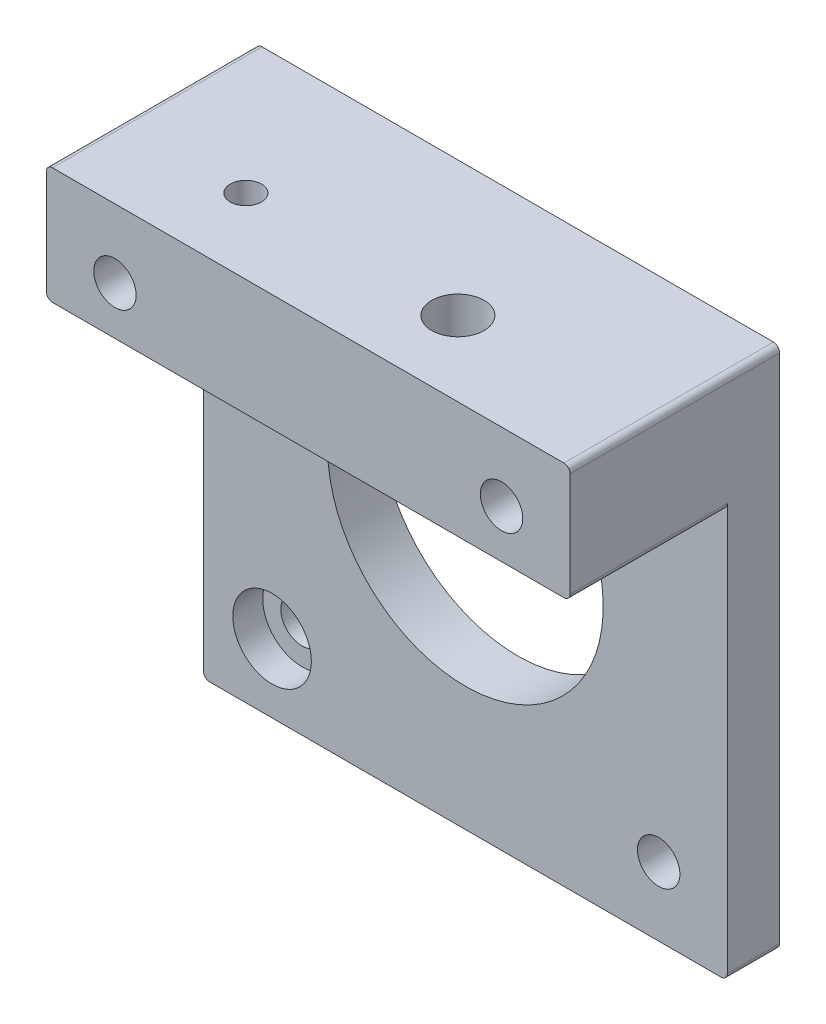
SolidWorks part; units mm, degrees
ref_plane "Front Plane" through (0, 0, 0) normal (0, 0, 1) x (1, 0, 0)
ref_plane "Top Plane" through (0, 0, 0) normal (0, 1, 0) x (1, 0, 0)
ref_plane "Right Plane" through (0, 0, 0) normal (1, 0, 0) x (0, 0, -1)
sketch "Sketch1" plane through (0, 0, 0) normal (0, 0, 1) x (1, 0, 0)
  line L1 (-21, 21) -> (21, 21)
  line L2 (-21, 21) -> (-21, -21)
  line L3 (-21, -21) -> (21, -21)
  line L4 (21, 21) -> (21, -21)
  line L5 (-21, 21) -> (21, -21) construction
  line L6 (-21, -21) -> (21, 21) construction
  point P0 (0, 0)
  dimension "D1" = 42
  dimension "D2" = 42
extrude "Boss-Extrude1" add sketch "Sketch1" along normal blind 16.8
sketch "Sketch2" plane through (0, 0, 16.8) normal (0, 0, 1) x (1, 0, 0)
  line L0 (21, -21) -> (21, 21) construction
  line L1 (-21, -21) -> (21, -21)
  line L2 (-21, -21) -> (-21, 11.65)
  line L3 (-21, 11.65) -> (21, 11.65)
  line L4 (21, -21) -> (21, 11.65)
  line L5 (21, 21) -> (-21, 21) construction
  dimension "D1" = 9.35
extrude "Cut-Extrude1" cut sketch "Sketch2" against normal blind 12.6
sketch "Sketch3" plane through (0, 0, 0) normal (0, 0, -1) x (-1, 0, 0)
  circle A0 centre (0, 0) radius 11.05
  dimension "D1" = 22.1
extrude "Cut-Extrude2" cut sketch "Sketch3" against normal up to next
hole_wizard "M3 Clearance Hole1" positions "Sketch4" profile "Sketch5" hole size "M3" standard "ISO" end condition up to next
sketch "Sketch4" plane through (0, 0, 16.8) normal (0, 0, 1) x (1, 0, 0)
  point P0 (15.5, 15.5)
  point P2 (-15.5, 15.5)
  point P4 (-15.5, -15.5)
  point P6 (15.5, -15.5)
  dimension "D1" = 15.5
  dimension "D2" = 15.5
  dimension "D3" = 15.5
  dimension "D4" = 15.5
sketch "Sketch5" plane through (15.5, 15.5, 16.8) normal (1, 0, 0) x (0, -1, 0)
  line L0 (0, 0) -> (0, 16.8)
  line L1 (0, 16.8) -> (1.7, 16.8)
  line L2 (1.7, 16.8) -> (1.7, 0)
  line L5 (1.7, 0) -> (0, 0)
  line L11 (0, -6.35) -> (0, 107.95) construction
  dimension "Thru Hole Dia." = 3.4
  dimension "Thru Hole Depth" = 16.8
sketch "Sketch6" plane through (0, 0, 4.2) normal (0, 0, 1) x (1, 0, 0)
  circle A0 centre (-15.5, -15.5) radius 3.15
  dimension "D1" = 6.3
extrude "Cut-Extrude3" cut sketch "Sketch6" against normal blind 2.4
hole_wizard "M5 Tapped Hole1" positions "Sketch7" profile "Sketch8" tap size "M5" standard "ISO" end condition up to next
sketch "Sketch7" plane through (0, 21, 0) normal (0, 1, 0) x (1, 0, 0)
  line L0 (21, -16.8) -> (21, 0) construction
  line L1 (21, -16.8) -> (-21, -16.8) construction
  point P0 (6, -10.8)
  dimension "D1" = 15
  dimension "D2" = 6
sketch "Sketch8" plane through (6, 21, 10.8) normal (1, 0, 0) x (0, 0, 1)
  line L0 (0, 0) -> (0, 9.35)
  line L1 (0, 9.35) -> (2.1, 9.35)
  line L2 (2.1, 9.35) -> (2.1, 0)
  line L5 (2.1, 0) -> (0, 0)
  line L11 (0, -6.35) -> (0, 107.95) construction
  dimension "Thru Tap Drill Dia." = 4.2
  dimension "Thru Tap Drill Depth" = 9.35
cosmetic thread "Hole Thread1" parameters "D2"=5
hole_wizard "M3 Tapped Hole1" positions "Sketch9" profile "Sketch10" tap size "M3" standard "ISO" end condition up to next
sketch "Sketch9" plane through (0, 21, 0) normal (0, 1, 0) x (1, 0, 0)
  line L0 (-21, -16.8) -> (-21, 0) construction
  line L1 (21, -16.8) -> (-21, -16.8) construction
  point P0 (-11, -10.8)
  dimension "D1" = 10
  dimension "D2" = 6
sketch "Sketch10" plane through (-11, 21, 10.8) normal (1, 0, 0) x (0, 0, 1)
  line L0 (0, 0) -> (0, 9.35)
  line L1 (0, 9.35) -> (1.25, 9.35)
  line L2 (1.25, 9.35) -> (1.25, 0)
  line L5 (1.25, 0) -> (0, 0)
  line L11 (0, -6.35) -> (0, 107.95) construction
  dimension "Thru Tap Drill Dia." = 2.5
  dimension "Thru Tap Drill Depth" = 9.35
cosmetic thread "Hole Thread2" parameters "D2"=3
fillet "Fillet1" radius 0.5 6 edges at (-21, -21, 2.1) (21, -21, 2.1) (21, 21, 8.4) (21, 11.65, 10.5) (-21, 11.65, 10.5) (-21, 21, 8.4)
